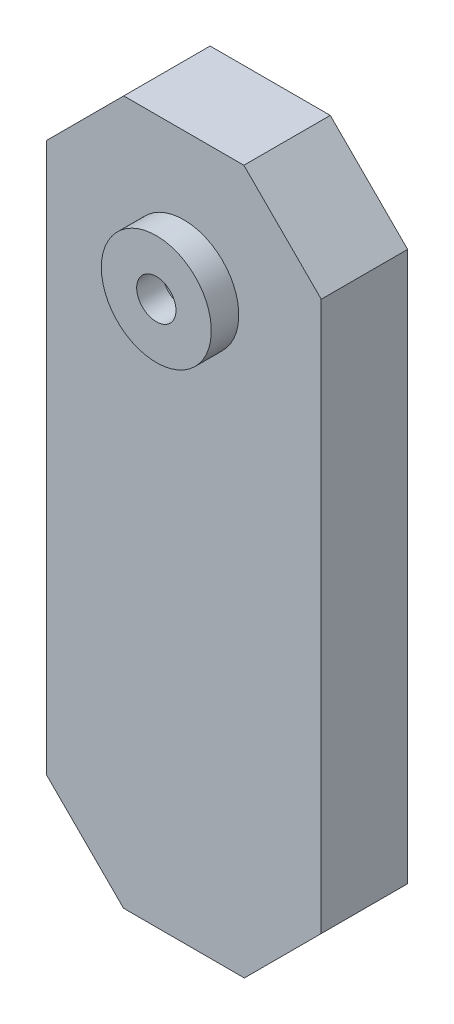
SolidWorks part; units mm, degrees
ref_plane "Спереди" through (0, 0, 0) normal (0, 0, 1) x (1, 0, 0)
ref_plane "Сверху" through (0, 0, 0) normal (0, 1, 0) x (1, 0, 0)
ref_plane "Справа" through (0, 0, 0) normal (1, 0, 0) x (0, 0, -1)
sketch "Эскиз1" plane through (0, 0, 0) normal (0, 0, 1) x (1, 0, 0)
  line L0 (105.0829, 581.7221) -> (45.979, 640.8259)
  line L1 (45.979, 640.8259) -> (-45.8132, 640.8259)
  line L2 (-45.8132, 640.8259) -> (-104.9171, 581.7221)
  line L3 (-104.9171, 581.7221) -> (-104.9171, 162.2129)
  line L4 (-104.9171, 162.2129) -> (-45.9732, 103.269)
  line L5 (-45.9732, 103.269) -> (46.3268, 103.269)
  line L6 (46.3268, 103.269) -> (105.0829, 162.0251)
  line L7 (105.0829, 162.0251) -> (105.0829, 581.7221)
  line L8 (0.0829, 640.8259) -> (0.0829, 703.4762) construction
  dimension "D1" = 105
  dimension "D2" = 105
extrude "Вытянуть1" add sketch "Эскиз1" along normal blind 66
ref_plane "Plane1" through (0, 490.8259, 0) normal (0, 1, 0) x (1, 0, 0)
sketch "Sketch1" plane through (0, 490.8259, 0) normal (0, 1, 0) x (1, 0, 0)
  line L0 (-104.9171, 0) -> (-164.2664, 0) construction
  line L1 (-104.9171, 0) -> (-104.9171, 70.7003) construction
  circle A0 centre (-108.4171, 0) radius 3.5
extrude "Boss-Extrude1" add sketch "Sketch1" along normal blind 50 separate body
sketch "Sketch2" plane through (0, 0, 66) normal (0, 0, 1) x (1, 0, 0)
  line L0 (0.0829, 640.8259) -> (0.0829, 440.9538) construction
  line L2 (45.979, 640.8259) -> (-45.8132, 640.8259) construction
  circle A0 centre (0.0829, 539.8259) radius 42
  dimension "D1" = 101
extrude "Boss-Extrude2" add sketch "Sketch2" along normal blind 21
sketch "Sketch3" plane through (0, 0, 87) normal (0, 0, 1) x (1, 0, 0)
  circle A0 centre (0.0829, 539.8259) radius 15
extrude "Cut-Extrude1" cut sketch "Sketch3" against normal blind 20
